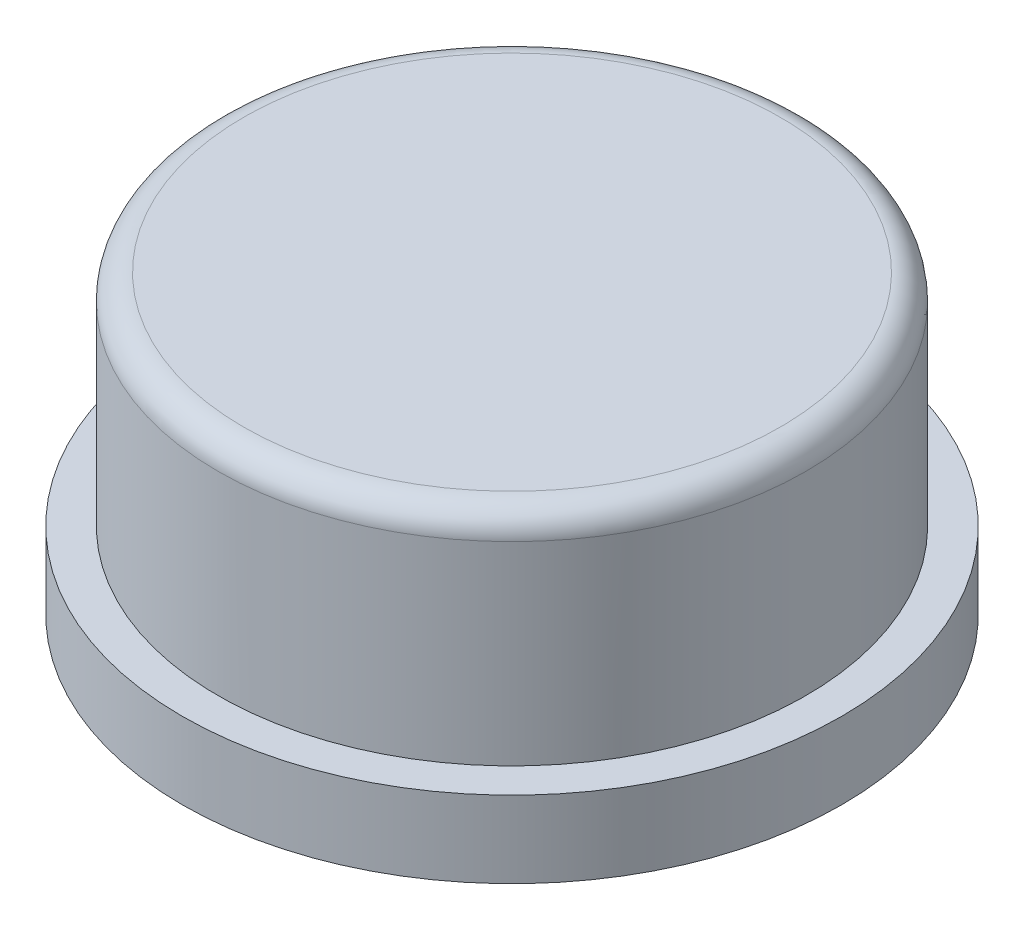
SolidWorks part; units mm, degrees
material "ABS"
ref_plane "Front Plane" through (0, 0, 0) normal (0, 0, 1) x (1, 0, 0)
ref_plane "Top Plane" through (0, 0, 0) normal (0, 1, 0) x (1, 0, 0)
ref_plane "Right Plane" through (0, 0, 0) normal (1, 0, 0) x (0, 0, -1)
sketch "Sketch1" plane through (0, 0, 0) normal (0, 1, 0) x (1, 0, 0)
  circle A0 centre (0, 0) radius 6.45
  dimension "D1" = 12.9
extrude "Boss-Extrude1" add sketch "Sketch1" along normal blind 1.5
sketch "Sketch2" plane through (0, 1.5, 0) normal (0, 1, 0) x (1, 0, 0)
  circle A0 centre (0, 0) radius 5.75
  dimension "D1" = 11.5
extrude "Boss-Extrude2" add sketch "Sketch2" along normal blind 4.3
fillet "Fillet1" radius 0.5 1 edges at (0, 5.8, 5.75)
